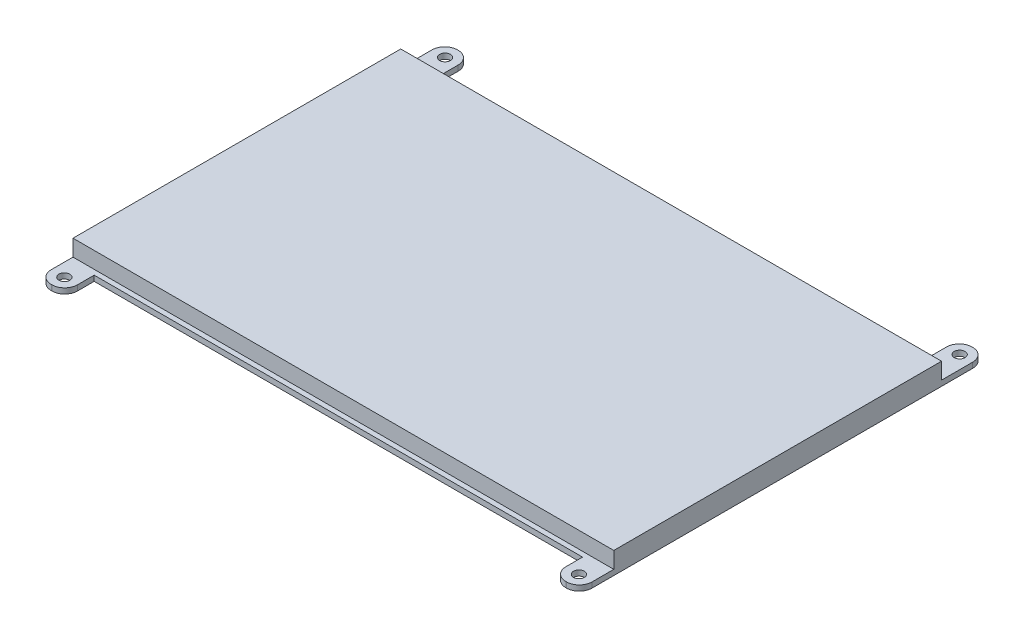
SolidWorks part; units mm, degrees
ref_plane "前视基准面" through (0, 0, 0) normal (0, 0, 1) x (1, 0, 0)
ref_plane "上视基准面" through (0, 0, 0) normal (0, 1, 0) x (1, 0, 0)
ref_plane "右视基准面" through (0, 0, 0) normal (1, 0, 0) x (0, 0, -1)
sketch "草图1" plane through (0, 0, 0) normal (0, 1, 0) x (1, 0, 0)
  line L1 (-73.7209, 50) -> (91.2791, 50)
  line L2 (-73.7209, 50) -> (-73.7209, -50)
  line L3 (-73.7209, -50) -> (91.2791, -50)
  line L4 (91.2791, 50) -> (91.2791, -50)
  dimension "D1" = 100
  dimension "D2" = 165
extrude "凸台-拉伸1" add sketch "草图1" along normal blind 5
sketch "草图2" plane through (0, 0, 0) normal (0, -1, 0) x (1, 0, 0)
  line L0 (-73.7209, 50) -> (-73.7209, 51.53)
  line L1 (-73.7209, -50) -> (-73.7209, -54.42)
  line L2 (87.3791, -59.52) -> (87.1791, -59.52) construction
  line L3 (91.2791, 50) -> (-73.7209, 50)
  line L4 (91.2791, 50) -> (91.2791, 51.53)
  line L5 (91.2791, 51.53) -> (-73.7209, 51.53)
  line L6 (-73.7209, 50) -> (-73.7209, 51.53)
  line L7 (91.2791, -50) -> (-73.7209, -50)
  line L8 (91.2791, -50) -> (91.2791, -54.42)
  line L9 (91.2791, -54.42) -> (-73.7209, -54.42)
  line L10 (-73.7209, -50) -> (-73.7209, -54.42)
  line L11 (-73.7209, 51.53) -> (-65.7209, 51.53)
  line L12 (-73.7209, 51.53) -> (-73.7209, 56.63)
  line L13 (-69.8209, 60.53) -> (-69.6209, 60.53)
  line L14 (-65.7209, 51.53) -> (-65.7209, 56.63)
  line L15 (91.2791, 51.53) -> (83.2791, 51.53)
  line L16 (91.2791, 51.53) -> (91.2791, 56.63)
  line L17 (87.3791, 60.53) -> (87.1791, 60.53)
  line L18 (83.2791, 51.53) -> (83.2791, 56.63)
  line L19 (91.2791, -54.42) -> (83.2791, -54.42)
  line L20 (91.2791, -54.42) -> (91.2791, -59.52)
  line L21 (87.3791, -63.42) -> (87.1791, -63.42)
  line L22 (83.2791, -54.42) -> (83.2791, -59.52)
  line L23 (-73.7209, -54.42) -> (-65.7209, -54.42)
  line L24 (-73.7209, -54.42) -> (-73.7209, -59.52)
  line L25 (-69.8209, -63.42) -> (-69.6209, -63.42)
  line L26 (-65.7209, -54.42) -> (-65.7209, -59.52)
  line L27 (-69.6209, -59.52) -> (-69.8209, -59.52) construction
  line L28 (-69.6209, 56.63) -> (-69.8209, 56.63) construction
  line L29 (87.3791, 56.63) -> (87.1791, 56.63) construction
  arc A0 (-73.7209, -59.52) -> (-69.8209, -63.42) centre (-69.8209, -59.52) ccw
  arc A1 (-69.6209, -63.42) -> (-65.7209, -59.52) centre (-69.6209, -59.52) ccw
  arc A2 (87.1791, -63.42) -> (83.2791, -59.52) centre (87.1791, -59.52) cw
  arc A3 (91.2791, -59.52) -> (87.3791, -63.42) centre (87.3791, -59.52) cw
  arc A4 (87.1791, 60.53) -> (83.2791, 56.63) centre (87.1791, 56.63) ccw
  arc A5 (91.2791, 56.63) -> (87.3791, 60.53) centre (87.3791, 56.63) ccw
  arc A6 (-73.7209, 56.63) -> (-69.8209, 60.53) centre (-69.8209, 56.63) cw
  arc A7 (-69.6209, 60.53) -> (-65.7209, 56.63) centre (-69.6209, 56.63) cw
  circle A8 centre (87.2791, -59.52) radius 1.65
  circle A9 centre (-69.7209, -59.52) radius 1.65
  circle A10 centre (-69.7209, 56.63) radius 1.65
  circle A11 centre (87.2791, 56.63) radius 1.65
  point P26 (-73.7209, -63.42)
  point P29 (-65.7209, -63.42)
  point P32 (83.2791, -63.42)
  point P35 (91.2791, -63.42)
  point P38 (83.2791, 60.53)
  point P41 (91.2791, 60.53)
  point P44 (-73.7209, 60.53)
  point P47 (-65.7209, 60.53)
  line M37 (-73.7209, 50) -> (-73.7209, -50)
  line M38 (-73.7209, -50) -> (91.2791, -50)
  line M39 (91.2791, -50) -> (91.2791, 50)
  line M40 (91.2791, 50) -> (-73.7209, 50)
  dimension "D11" = 3.9
  dimension "D12" = 3.3
  dimension "D13" = 3.3
  dimension "D14" = 3.3
  dimension "D15" = 3.3
  dimension "D1" = 1.53
  dimension "D2" = 4.42
  dimension "D3" = 9
  dimension "D4" = 8
  dimension "D5" = 8
  dimension "D6" = 9
  dimension "D7" = 8
  dimension "D8" = 9
  dimension "D9" = 9
  dimension "D10" = 8
extrude "凸台-拉伸2" add sketch "草图2" along normal blind 1.65 contours L16 A5 L17 A4 L18 L5 A11 | L4 L5 L0 M40 | A7 L13 A6 L12 L5 L14 A10 | L25 A1 L26 L9 L24 A0 A9 | L9 L8 L1 M38 | A3 L20 L9 L22 A2 L21 A8 | M40 M37 M38 M39
